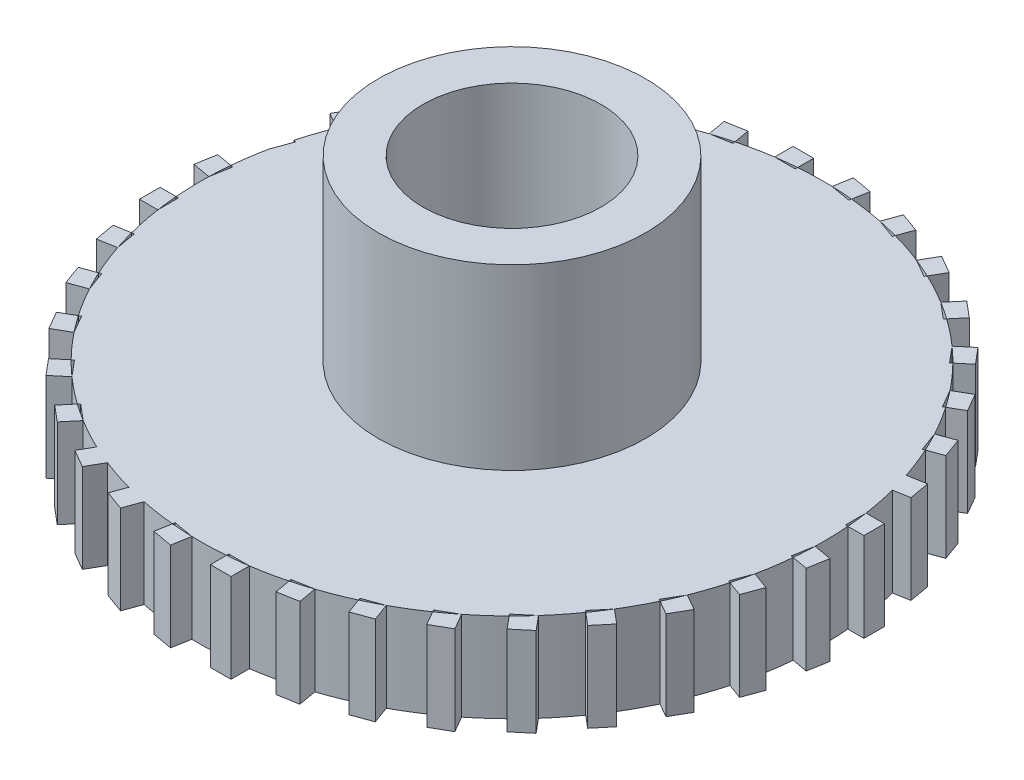
SolidWorks part; units mm, degrees
ref_plane "Front Plane" through (0, 0, 0) normal (0, 0, 1) x (1, 0, 0)
ref_plane "Top Plane" through (0, 0, 0) normal (0, 1, 0) x (1, 0, 0)
ref_plane "Right Plane" through (0, 0, 0) normal (1, 0, 0) x (0, 0, -1)
sketch "Sketch1" plane through (0, 0, 0) normal (0, 1, 0) x (1, 0, 0)
  line L0 (-22.2167, 0.6064) -> (-21.9619, 2.0517)
  line L1 (-21.9845, -3.2607) -> (-23.297, -3.2607)
  line L2 (-21.9845, -3.2607) -> (-21.9845, -1.7931)
  line L3 (-21.9845, -1.7931) -> (-23.297, -1.7931)
  line L4 (-23.297, -3.2607) -> (-23.297, -1.7931)
  line L5 (-22.2167, 0.6064) -> (-23.5093, 0.8343)
  line L6 (-23.5093, 0.8343) -> (-23.2544, 2.2796)
  line L7 (-21.9619, 2.0517) -> (-23.2544, 2.2796)
  line L8 (-21.7739, 4.455) -> (-21.2719, 5.8342)
  line L9 (-21.7739, 4.455) -> (-23.0072, 4.9039)
  line L10 (-23.0072, 4.9039) -> (-22.5053, 6.2831)
  line L11 (-21.2719, 5.8342) -> (-22.5053, 6.2831)
  line L12 (-20.6695, 8.1684) -> (-19.9357, 9.4394)
  line L13 (-20.6695, 8.1684) -> (-21.8062, 8.8246)
  line L14 (-21.8062, 8.8246) -> (-21.0723, 10.0956)
  line L15 (-19.9357, 9.4394) -> (-21.0723, 10.0956)
  line L16 (-18.9371, 11.6335) -> (-17.9937, 12.7578)
  line L17 (-18.9371, 11.6335) -> (-19.9425, 12.4771)
  line L18 (-19.9425, 12.4771) -> (-18.9991, 13.6014)
  line L19 (-17.9937, 12.7578) -> (-18.9991, 13.6014)
  line L20 (-16.6292, 14.7451) -> (-15.505, 15.6885)
  line L21 (-16.6292, 14.7451) -> (-17.4729, 15.7506)
  line L22 (-17.4729, 15.7506) -> (-16.3486, 16.6939)
  line L23 (-15.505, 15.6885) -> (-16.3486, 16.6939)
  line L24 (-13.8161, 17.4088) -> (-12.5451, 18.1426)
  line L25 (-13.8161, 17.4088) -> (-14.4724, 18.5454)
  line L26 (-14.4724, 18.5454) -> (-13.2014, 19.2792)
  line L27 (-12.5451, 18.1426) -> (-13.2014, 19.2792)
  line L28 (-10.5832, 19.5434) -> (-9.2041, 20.0454)
  line L29 (-10.5832, 19.5434) -> (-11.0321, 20.7768)
  line L30 (-11.0321, 20.7768) -> (-9.653, 21.2787)
  line L31 (-9.2041, 20.0454) -> (-9.653, 21.2787)
  line L32 (-7.0288, 21.0843) -> (-5.5834, 21.3391)
  line L33 (-7.0288, 21.0843) -> (-7.2567, 22.3768)
  line L34 (-7.2567, 22.3768) -> (-5.8113, 22.6317)
  line L35 (-5.5834, 21.3391) -> (-5.8113, 22.6317)
  line L36 (-3.2607, 21.9845) -> (-1.7931, 21.9845)
  line L37 (-3.2607, 21.9845) -> (-3.2607, 23.297)
  line L38 (-3.2607, 23.297) -> (-1.7931, 23.297)
  line L39 (-1.7931, 21.9845) -> (-1.7931, 23.297)
  line L40 (0.6064, 22.2167) -> (2.0517, 21.9619)
  line L41 (0.6064, 22.2167) -> (0.8343, 23.5093)
  line L42 (0.8343, 23.5093) -> (2.2796, 23.2544)
  line L43 (2.0517, 21.9619) -> (2.2796, 23.2544)
  line L44 (4.455, 21.7739) -> (5.8342, 21.2719)
  line L45 (4.455, 21.7739) -> (4.9039, 23.0072)
  line L46 (4.9039, 23.0072) -> (6.2831, 22.5053)
  line L47 (5.8342, 21.2719) -> (6.2831, 22.5053)
  line L48 (8.1684, 20.6695) -> (9.4394, 19.9357)
  line L49 (8.1684, 20.6695) -> (8.8246, 21.8062)
  line L50 (8.8246, 21.8062) -> (10.0956, 21.0723)
  line L51 (9.4394, 19.9357) -> (10.0956, 21.0723)
  line L52 (11.6335, 18.9371) -> (12.7578, 17.9937)
  line L53 (11.6335, 18.9371) -> (12.4771, 19.9425)
  line L54 (12.4771, 19.9425) -> (13.6014, 18.9991)
  line L55 (12.7578, 17.9937) -> (13.6014, 18.9991)
  line L56 (14.7451, 16.6292) -> (15.6885, 15.505)
  line L57 (14.7451, 16.6292) -> (15.7506, 17.4729)
  line L58 (15.7506, 17.4729) -> (16.6939, 16.3486)
  line L59 (15.6885, 15.505) -> (16.6939, 16.3486)
  line L60 (17.4088, 13.8161) -> (18.1426, 12.5451)
  line L61 (17.4088, 13.8161) -> (18.5454, 14.4724)
  line L62 (18.5454, 14.4724) -> (19.2792, 13.2014)
  line L63 (18.1426, 12.5451) -> (19.2792, 13.2014)
  line L64 (19.5434, 10.5832) -> (20.0454, 9.2041)
  line L65 (19.5434, 10.5832) -> (20.7768, 11.0321)
  line L66 (20.7768, 11.0321) -> (21.2787, 9.653)
  line L67 (20.0454, 9.2041) -> (21.2787, 9.653)
  line L68 (21.0843, 7.0288) -> (21.3391, 5.5834)
  line L69 (21.0843, 7.0288) -> (22.3768, 7.2567)
  line L70 (22.3768, 7.2567) -> (22.6317, 5.8113)
  line L71 (21.3391, 5.5834) -> (22.6317, 5.8113)
  line L72 (21.9845, 3.2607) -> (21.9845, 1.7931)
  line L73 (21.9845, 3.2607) -> (23.297, 3.2607)
  line L74 (23.297, 3.2607) -> (23.297, 1.7931)
  line L75 (21.9845, 1.7931) -> (23.297, 1.7931)
  line L76 (22.2167, -0.6064) -> (21.9619, -2.0517)
  line L77 (22.2167, -0.6064) -> (23.5093, -0.8343)
  line L78 (23.5093, -0.8343) -> (23.2544, -2.2796)
  line L79 (21.9619, -2.0517) -> (23.2544, -2.2796)
  line L80 (21.7739, -4.455) -> (21.2719, -5.8342)
  line L81 (21.7739, -4.455) -> (23.0072, -4.9039)
  line L82 (23.0072, -4.9039) -> (22.5053, -6.2831)
  line L83 (21.2719, -5.8342) -> (22.5053, -6.2831)
  line L84 (20.6695, -8.1684) -> (19.9357, -9.4394)
  line L85 (20.6695, -8.1684) -> (21.8062, -8.8246)
  line L86 (21.8062, -8.8246) -> (21.0723, -10.0956)
  line L87 (19.9357, -9.4394) -> (21.0723, -10.0956)
  line L88 (18.9371, -11.6335) -> (17.9937, -12.7578)
  line L89 (18.9371, -11.6335) -> (19.9425, -12.4771)
  line L90 (19.9425, -12.4771) -> (18.9991, -13.6014)
  line L91 (17.9937, -12.7578) -> (18.9991, -13.6014)
  line L92 (16.6292, -14.7451) -> (15.505, -15.6885)
  line L93 (16.6292, -14.7451) -> (17.4729, -15.7506)
  line L94 (17.4729, -15.7506) -> (16.3486, -16.6939)
  line L95 (15.505, -15.6885) -> (16.3486, -16.6939)
  line L96 (13.8161, -17.4088) -> (12.5451, -18.1426)
  line L97 (13.8161, -17.4088) -> (14.4724, -18.5454)
  line L98 (14.4724, -18.5454) -> (13.2014, -19.2792)
  line L99 (12.5451, -18.1426) -> (13.2014, -19.2792)
  line L100 (10.5832, -19.5434) -> (9.2041, -20.0454)
  line L101 (10.5832, -19.5434) -> (11.0321, -20.7768)
  line L102 (11.0321, -20.7768) -> (9.653, -21.2787)
  line L103 (9.2041, -20.0454) -> (9.653, -21.2787)
  line L104 (7.0288, -21.0843) -> (5.5834, -21.3391)
  line L105 (7.0288, -21.0843) -> (7.2567, -22.3768)
  line L106 (7.2567, -22.3768) -> (5.8113, -22.6317)
  line L107 (5.5834, -21.3391) -> (5.8113, -22.6317)
  line L108 (3.2607, -21.9845) -> (1.7931, -21.9845)
  line L109 (3.2607, -21.9845) -> (3.2607, -23.297)
  line L110 (3.2607, -23.297) -> (1.7931, -23.297)
  line L111 (1.7931, -21.9845) -> (1.7931, -23.297)
  line L112 (-0.6064, -22.2167) -> (-2.0517, -21.9619)
  line L113 (-0.6064, -22.2167) -> (-0.8343, -23.5093)
  line L114 (-0.8343, -23.5093) -> (-2.2796, -23.2544)
  line L115 (-2.0517, -21.9619) -> (-2.2796, -23.2544)
  line L116 (-4.455, -21.7739) -> (-5.8342, -21.2719)
  line L117 (-4.455, -21.7739) -> (-4.9039, -23.0072)
  line L118 (-4.9039, -23.0072) -> (-6.2831, -22.5053)
  line L119 (-5.8342, -21.2719) -> (-6.2831, -22.5053)
  line L120 (-8.1684, -20.6695) -> (-9.4394, -19.9357)
  line L121 (-8.1684, -20.6695) -> (-8.8246, -21.8062)
  line L122 (-8.8246, -21.8062) -> (-10.0956, -21.0723)
  line L123 (-9.4394, -19.9357) -> (-10.0956, -21.0723)
  line L124 (-11.6335, -18.9371) -> (-12.7578, -17.9937)
  line L125 (-11.6335, -18.9371) -> (-12.4771, -19.9425)
  line L126 (-12.4771, -19.9425) -> (-13.6014, -18.9991)
  line L127 (-12.7578, -17.9937) -> (-13.6014, -18.9991)
  line L128 (-14.7451, -16.6292) -> (-15.6885, -15.505)
  line L129 (-14.7451, -16.6292) -> (-15.7506, -17.4729)
  line L130 (-15.7506, -17.4729) -> (-16.6939, -16.3486)
  line L131 (-15.6885, -15.505) -> (-16.6939, -16.3486)
  line L132 (-17.4088, -13.8161) -> (-18.1426, -12.5451)
  line L133 (-17.4088, -13.8161) -> (-18.5454, -14.4724)
  line L134 (-18.5454, -14.4724) -> (-19.2792, -13.2014)
  line L135 (-18.1426, -12.5451) -> (-19.2792, -13.2014)
  line L136 (-19.5434, -10.5832) -> (-20.0454, -9.2041)
  line L137 (-19.5434, -10.5832) -> (-20.7768, -11.0321)
  line L138 (-20.7768, -11.0321) -> (-21.2787, -9.653)
  line L139 (-20.0454, -9.2041) -> (-21.2787, -9.653)
  line L140 (-21.0843, -7.0288) -> (-21.3391, -5.5834)
  line L141 (-21.0843, -7.0288) -> (-22.3768, -7.2567)
  line L142 (-22.3768, -7.2567) -> (-22.6317, -5.8113)
  line L143 (-21.3391, -5.5834) -> (-22.6317, -5.8113)
  circle A0 centre (0, 0) radius 22.225
  circle A1 centre (0, 0) radius 6.35
  point P150 (-1.9274, -4.9818)
  point P151 (0, 0)
  dimension "D1" = 12.7
  dimension "D2" = 44.45
  dimension "D3" = 36
extrude "Boss-Extrude1" add sketch "Sketch1" along normal blind 6.35
sketch "Sketch2" plane through (0, 6.35, 0) normal (0, 1, 0) x (1, 0, 0)
  circle A0 centre (0, 0) radius 6.35
  circle A1 centre (0, 0) radius 9.525
  dimension "D1" = 19.05
extrude "Boss-Extrude2" add sketch "Sketch2" along normal blind 12.7
